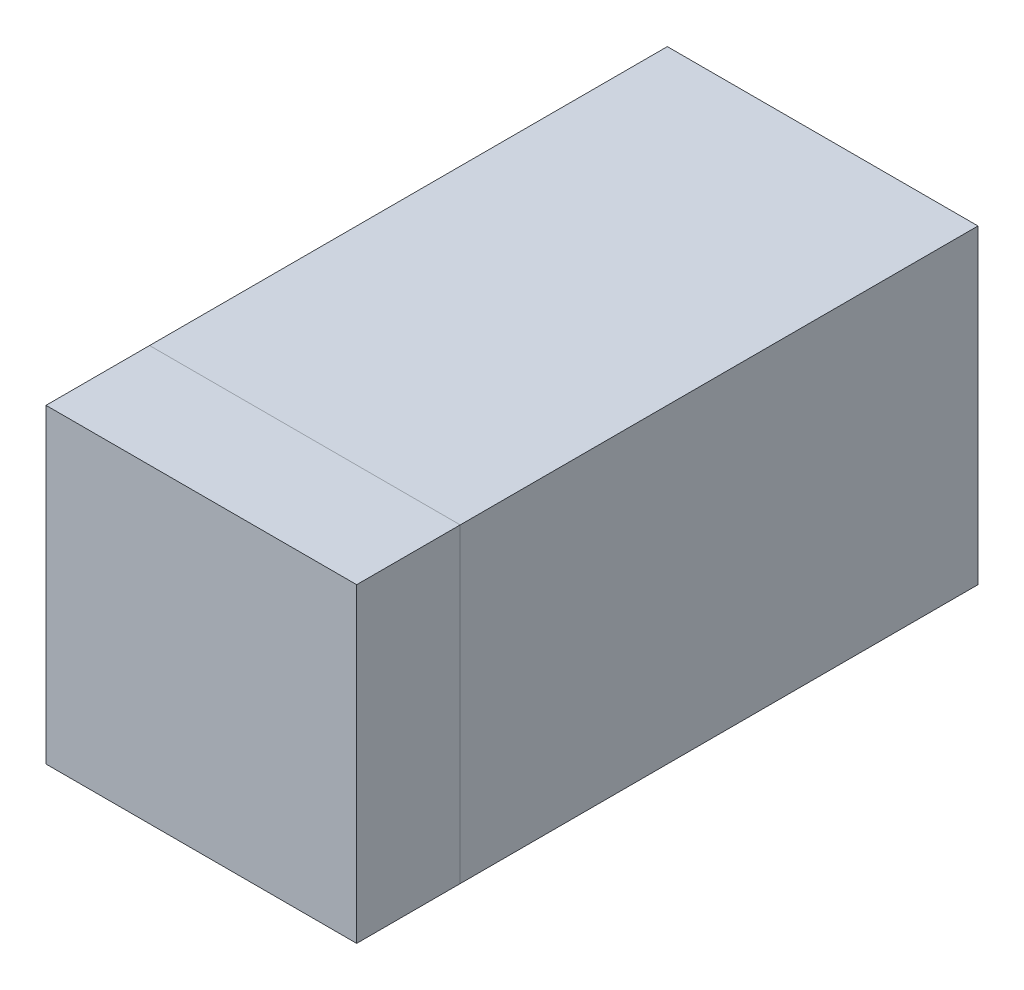
SolidWorks part; units mm, degrees
ref_plane "Front Plane" through (0, 0, 0) normal (0, 0, 1) x (1, 0, 0)
ref_plane "Top Plane" through (0, 0, 0) normal (0, 1, 0) x (1, 0, 0)
ref_plane "Right Plane" through (0, 0, 0) normal (1, 0, 0) x (0, 0, -1)
sketch "Sketch1" plane through (0, 0, 0) normal (0, 0, 1) x (1, 0, 0)
  line L1 (0, 0) -> (76.2, 0)
  line L2 (0, 0) -> (0, 76.2)
  line L3 (0, 76.2) -> (76.2, 76.2)
  line L4 (76.2, 0) -> (76.2, 76.2)
  dimension "D1" = 76.2
  dimension "D2" = 76.2
extrude "Boss-Extrude1" add sketch "Sketch1" along normal blind 127
sketch "Sketch4" plane through (0, 0, 127) normal (0, 0, 1) x (1, 0, 0)
  line L1 (0, 0) -> (76.2, 0)
  line L2 (0, 0) -> (0, 76.2)
  line L3 (0, 76.2) -> (76.2, 76.2)
  line L4 (76.2, 0) -> (76.2, 76.2)
extrude "Boss-Extrude4" add sketch "Sketch4" along normal blind 25.4 separate body
ref_plane "Plane2" through (38.1, 0, 0) normal (-1, 0, 0) x (0, 0, 1)
sketch "Sketch2" plane through (0, 0, 0) normal (0, -1, 0) x (1, 0, 0)
  line L0 (0, 127) -> (0, 0) construction
  line L1 (12.7, 12.7) -> (28.575, 12.7)
  line L2 (12.7, 12.7) -> (12.7, 139.7)
  line L3 (12.7, 139.7) -> (28.575, 139.7)
  line L4 (28.575, 12.7) -> (28.575, 139.7)
  line L5 (47.625, 139.7) -> (63.5, 139.7)
  line L6 (47.625, 139.7) -> (47.625, 12.7)
  line L7 (47.625, 12.7) -> (63.5, 12.7)
  line L8 (63.5, 139.7) -> (63.5, 12.7)
  line L9 (76.2, 127) -> (76.2, 0) construction
  line L10 (0, 0) -> (76.2, 0) construction
  line L11 (0, 127) -> (76.2, 127) construction
  dimension "D1" = 12.7
  dimension "D2" = 12.7
  dimension "D3" = 19.05
  dimension "D4" = 12.7
  dimension "D5" = 12.7
  dimension "D6" = 12.7
  dimension "D7" = 12.7
  dimension "D8" = 15.875
extrude "Boss-Extrude3" add sketch "Sketch2" along normal blind 2.54 separate body
